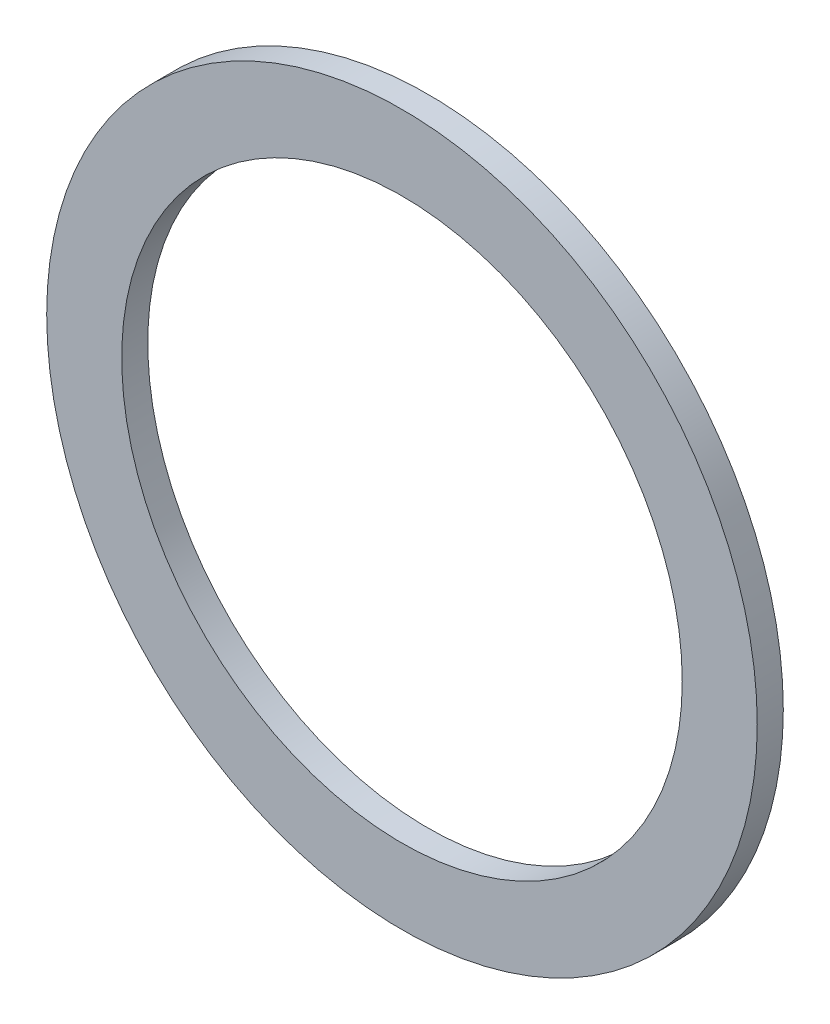
SolidWorks part; units mm, degrees
ref_plane "Plan1" through (0, 0, 0) normal (0, 0, 1) x (1, 0, 0)
ref_plane "Plan2" through (0, 0, 0) normal (0, 1, 0) x (1, 0, 0)
ref_plane "Plan3" through (0, 0, 0) normal (1, 0, 0) x (0, 0, -1)
sketch "Esquisse1" plane through (0, 0, 0) normal (0, 0, 1) x (1, 0, 0)
  circle A0 centre (0, 0) radius 22.5
  circle A1 centre (0, 0) radius 17.75
  dimension "D1" = 45
  dimension "D2" = 35.5
extrude "Base-Extrusion" add sketch "Esquisse1" along normal blind 1.65
